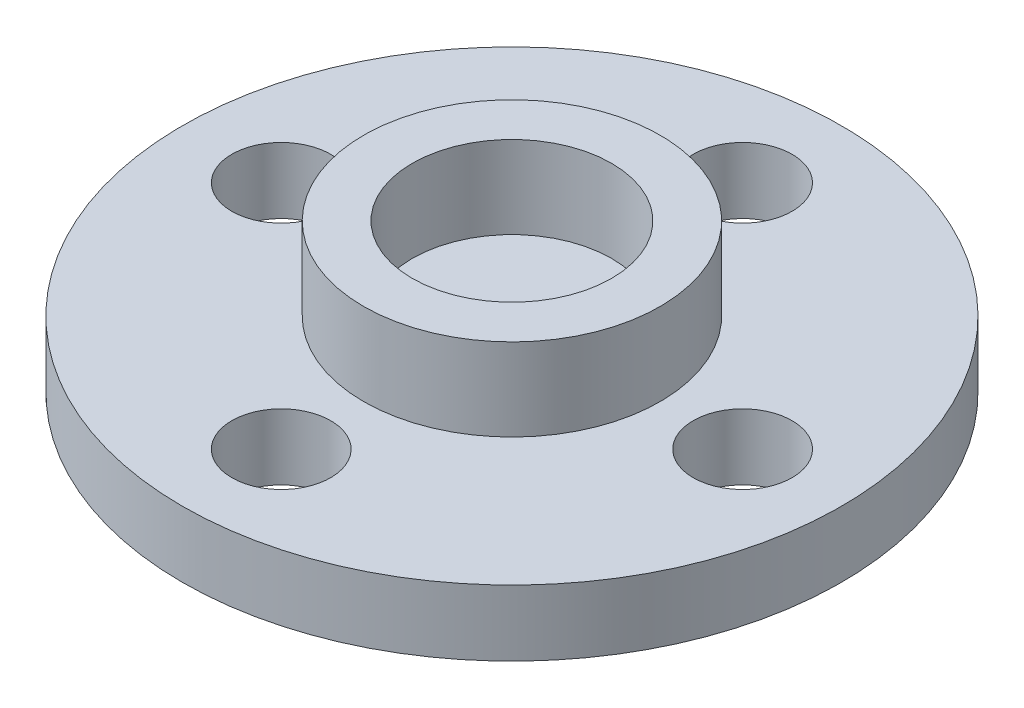
SolidWorks part; units mm, degrees
ref_plane "Alzado" through (0, 0, 0) normal (0, 0, 1) x (1, 0, 0)
ref_plane "Planta" through (0, 0, 0) normal (0, 1, 0) x (1, 0, 0)
ref_plane "Vista lateral" through (0, 0, 0) normal (1, 0, 0) x (0, 0, -1)
sketch "Croquis1" plane through (0, 0, 0) normal (0, 1, 0) x (1, 0, 0)
  circle A0 centre (0, 0) radius 10
  dimension "D1" = 20
extrude "Saliente-Extruir1" add sketch "Croquis1" along normal blind 2
sketch "Croquis2" plane through (0, 2, 0) normal (0, 1, 0) x (1, 0, 0)
  circle A0 centre (0, 0) radius 4.5
  dimension "D1" = 9
extrude "Saliente-Extruir2" add sketch "Croquis2" along normal blind 2.5
hole_wizard "Diámetro de taladro Ø3.0 (3)1" positions "Croquis3" profile "Croquis4" hole size "Ø3.0" standard "ISO"
sketch "Croquis3" plane through (0, 2, 0) normal (0, 1, 0) x (1, 0, 0)
  line L0 (0, 0) -> (0, 50000) construction
  line L1 (-1000, 0) -> (49000, 0) construction
  circle A0 centre (0, 0) radius 7 construction
  point P0 (0, 7)
  point P2 (-7, 0)
  point P4 (7, 0)
  point P6 (0, -7)
  dimension "D1" = 14
sketch "Croquis4" plane through (0, 2, -7) normal (1, 0, 0) x (0, 0, 1)
  line L0 (0, 0) -> (0, 50.9013)
  line L1 (0, 50.9013) -> (1.5, 50)
  line L2 (1.5, 50) -> (1.5, 0)
  line L5 (1.5, 0) -> (0, 0)
  line L10 (0, 50.9013) -> (-1.5, 50) construction
  line L11 (0, -6.35) -> (0, 107.95) construction
  dimension "Diámetro de taladro" = 3
  dimension "Profundidad de taladro" = 50
  dimension "Ángulo de perforador" = 118
sketch "Croquis5" plane through (0, 4.5, 0) normal (0, 1, 0) x (1, 0, 0)
  circle A0 centre (0, 0) radius 3.025
  dimension "D1" = 6.05
extrude "Cortar-Extruir1" cut sketch "Croquis5" against normal up to surface (2.5 mm away) up to face at (0, 2, -5.5)
